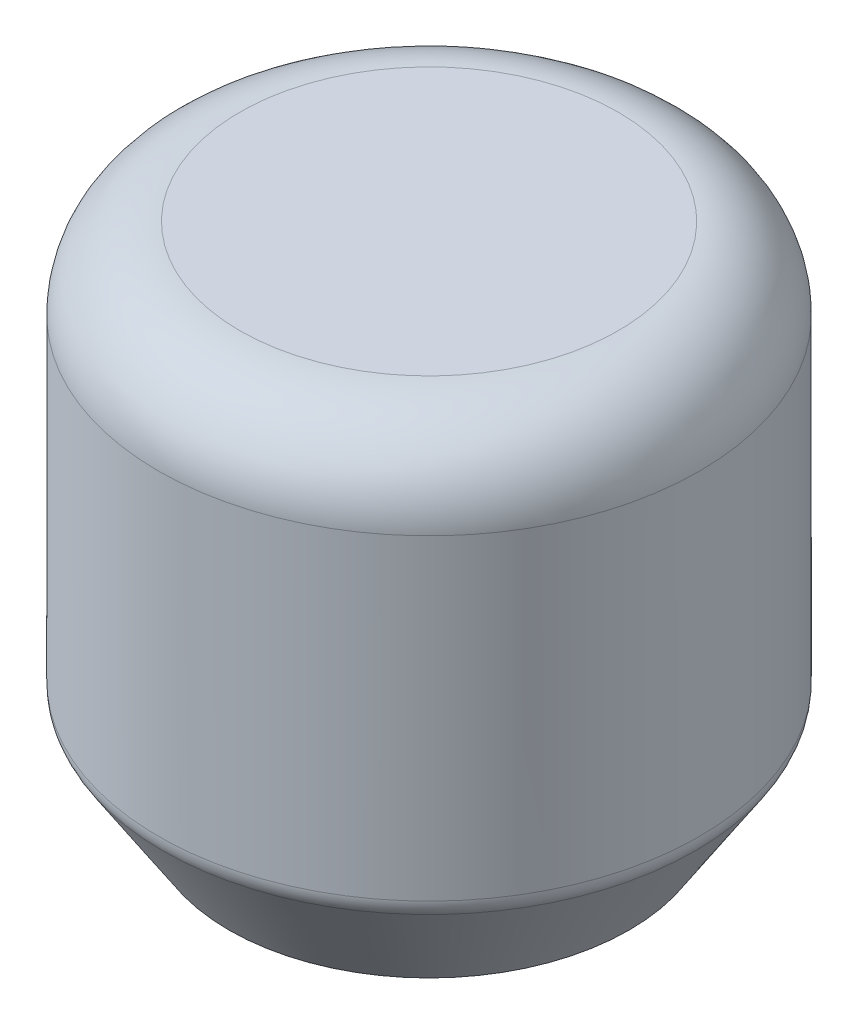
SolidWorks part; units mm, degrees
ref_plane "Front Plane" through (0, 0, 0) normal (0, 0, 1) x (1, 0, 0)
ref_plane "Top Plane" through (0, 0, 0) normal (0, 1, 0) x (1, 0, 0)
ref_plane "Right Plane" through (0, 0, 0) normal (1, 0, 0) x (0, 0, -1)
sketch "Sketch1" plane through (0, 0, 0) normal (0, 1, 0) x (1, 0, 0)
  circle A1 centre (0, 0) radius 127
extrude "Boss-Extrude1" add sketch "Sketch1" along normal blind 241.3 contours A1
fillet "Fillet1" radius 38.1 1 edges at (0, 241.3, 127)
chamfer "Chamfer1" distance 33.02 angle 57 1 edges at (0, 0, 127)
fillet "Fillet2" radius 12.7 1 edges at (0, 50.8463, 127)
